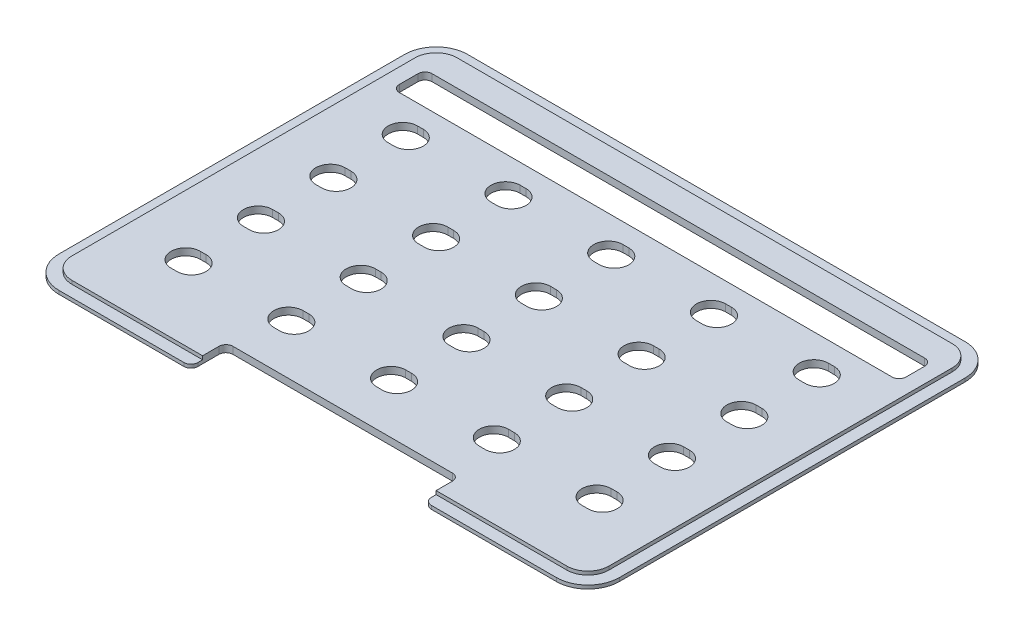
SolidWorks part; units mm, degrees
ref_plane "Front Plane" through (0, 0, 0) normal (0, 0, 1) x (1, 0, 0)
ref_plane "Top Plane" through (0, 0, 0) normal (0, 1, 0) x (1, 0, 0)
ref_plane "Right Plane" through (0, 0, 0) normal (1, 0, 0) x (0, 0, -1)
sketch "Sketch1" plane through (0, 0, 0) normal (0, 1, 0) x (1, 0, 0)
  line L1 (-120, -87.5) -> (120, -87.5)
  line L2 (-120, -87.5) -> (-120, 87.5)
  line L3 (-120, 87.5) -> (120, 87.5)
  line L4 (120, -87.5) -> (120, 87.5)
  line L5 (-120, -87.5) -> (120, 87.5) construction
  line L6 (-120, 87.5) -> (120, -87.5) construction
  point P0 (0, 0)
  dimension "D1" = 240
  dimension "D2" = 175
extrude "Outer Profile" add sketch "Sketch1" along normal blind 1.5
sketch "Sketch2" plane through (0, 1.5, 0) normal (0, 1, 0) x (1, 0, 0)
  line L0 (-120, 87.5) -> (-120, -87.5) construction
  line L1 (-115, -82.5) -> (115, -82.5)
  line L2 (-115, -82.5) -> (-115, 82.5)
  line L3 (-115, 82.5) -> (115, 82.5)
  line L4 (115, -82.5) -> (115, 82.5)
  line L5 (-115, -82.5) -> (115, 82.5) construction
  line L6 (-115, 82.5) -> (115, -82.5) construction
  line L7 (120, 87.5) -> (-120, 87.5) construction
  point P0 (0, 0)
  dimension "D1" = 5
  dimension "D2" = 5
extrude "Inner Profile" add sketch "Sketch2" along normal blind 1.5
fillet "Fillet1" radius 9 4 edges at (115, 2.25, 82.5) (115, 2.25, -82.5) (-115, 2.25, -82.5) (-115, 2.25, 82.5)
fillet "Fillet2" radius 13.5 4 edges at (-120, 0.75, -87.5) (120, 0.75, -87.5) (120, 0.75, 87.5) (-120, 0.75, 87.5)
sketch "Sketch3" plane through (0, 3, 0) normal (0, 1, 0) x (1, 0, 0)
  line L0 (0, 0) -> (0, -50000) construction
  line L1 (-108.5, -67.75) -> (108.5, -67.75) construction
  line L2 (-108.5, -67.75) -> (-108.5, 67.75) construction
  line L3 (-108.5, 67.75) -> (108.5, 67.75) construction
  line L4 (108.5, -67.75) -> (108.5, 67.75) construction
  line L5 (-108.5, -67.75) -> (108.5, 67.75) construction
  line L6 (-108.5, 67.75) -> (108.5, -67.75) construction
  line L7 (-1.25, -50.5) -> (1.25, -50.5) construction
  line L8 (-1.25, -44.25) -> (1.25, -44.25)
  line L9 (-1.25, -56.75) -> (1.25, -56.75)
  line L10 (-106, -82.5) -> (106, -82.5) construction
  arc A0 (-1.25, -44.25) -> (-1.25, -56.75) centre (-1.25, -50.5) ccw
  arc A1 (1.25, -56.75) -> (1.25, -44.25) centre (1.25, -50.5) ccw
  point P0 (0, 0)
  point P5 (0, -50.5)
  point P9 (0, -50.5)
  dimension "D6" = 15
  dimension "D1" = 217
  dimension "D2" = 135.5
  dimension "D3" = 32
  dimension "D5" = 12.5
chamfer "Chamfer" [suppressed] distance 0.5 angle 45
extrude "Cutout" cut sketch "Sketch3" against normal through all
pattern_linear "Cutouts" count 3 spacing 44 along (-1, 0, 0) count 4 spacing 31 along (0, 0, -1) of "Cutout"
mirror "Mirror1" about plane through (0, 0, 0) normal (1, 0, 0) of "Cutouts"
sketch "Sketch4" plane through (0, 3, 0) normal (0, 1, 0) x (1, 0, 0)
  line L0 (0, 82.5) -> (0, 0) construction
  line L1 (-108.5, 57.25) -> (108.5, 57.25)
  line L2 (-108.5, 57.25) -> (-108.5, 71.25)
  line L3 (-108.5, 71.25) -> (108.5, 71.25)
  line L4 (108.5, 57.25) -> (108.5, 71.25)
  line L5 (106, 82.5) -> (-106, 82.5) construction
  line L7 (-108.5, 67.75) -> (108.5, 67.75) construction
  dimension "D1" = 3.5
  dimension "D2" = 14
  dimension "D3" = 217
extrude "Message Window" cut sketch "Sketch4" against normal through all
fillet "Message Window Corners" radius 3 4 edges at (108.5, 1.5, -57.25) (-108.5, 1.5, -57.25) (108.5, 1.5, -71.25) (-108.5, 1.5, -71.25)
sketch "Sketch6" plane through (0, 3, 0) normal (0, 1, 0) x (1, 0, 0)
  line L0 (-106.5, -87.5) -> (106.5, -87.5) construction
  line L1 (-50, -87.5) -> (50, -87.5)
  line L2 (-50, -87.5) -> (-50, -72.5)
  line L3 (-50, -72.5) -> (50, -72.5)
  line L4 (50, -87.5) -> (50, -72.5)
  line L5 (-50, -87.5) -> (50, -72.5) construction
  line L6 (-50, -72.5) -> (50, -87.5) construction
  point P0 (0, -80)
  dimension "D1" = 100
  dimension "D2" = 15
extrude "Base Cutback" cut sketch "Sketch6" against normal through all
fillet "Fillet5" radius 3 4 edges at (-50, 0.75, 87.5) (50, 0.75, 87.5) (50, 1.5, 72.5) (-50, 1.5, 72.5)
chamfer "Edge Chamfer" [suppressed] distance 1 angle 45
